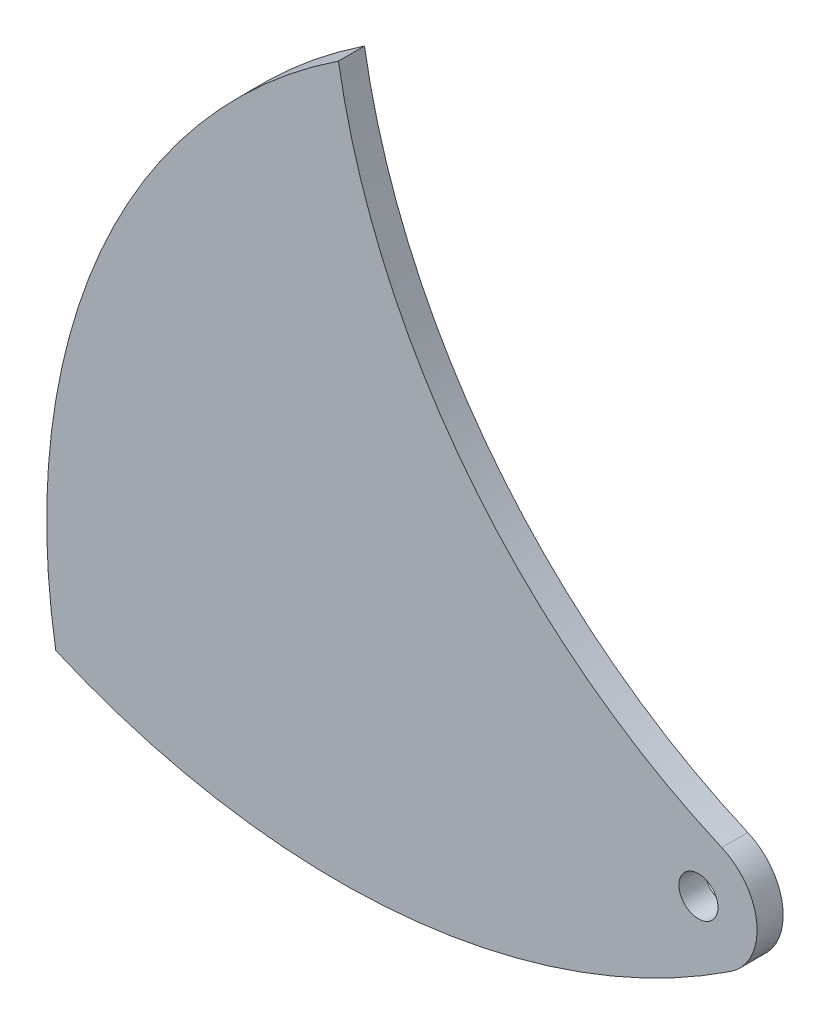
SolidWorks part; units mm, degrees
ref_plane "Front Plane" through (0, 0, 0) normal (0, 0, 1) x (1, 0, 0)
ref_plane "Top Plane" through (0, 0, 0) normal (0, 1, 0) x (1, 0, 0)
ref_plane "Right Plane" through (0, 0, 0) normal (1, 0, 0) x (0, 0, -1)
sketch "Sketch1" plane through (0, 0, 0) normal (0, 0, 1) x (1, 0, 0)
  circle A10 centre (0, 0) radius 0.75
  arc A11 (1.2428, -1.8756) -> (0.8953, 2.0642) centre (0, 0) ccw
  arc A15 (-13.8089, 20.8402) -> (-24.6515, -4.1598) centre (0, 0) ccw
  arc A16 (-13.8089, 20.8402) -> (0.8953, 2.0642) centre (10.8426, 25) ccw
  arc A17 (-24.6515, -4.1598) -> (1.2428, -1.8756) centre (-13.8089, 20.8402) ccw
  point P9 (0, 0)
  point P10 (0, 0)
  point P11 (0, 0)
  point P12 (0, 25)
  point P13 (0, 0)
  point P14 (0, 0)
  dimension "D1" = 1.5
  dimension "D5" = 4.5
  dimension "D3" = 25
extrude "Boss-Extrude1" add sketch "Sketch1" along normal blind 1
